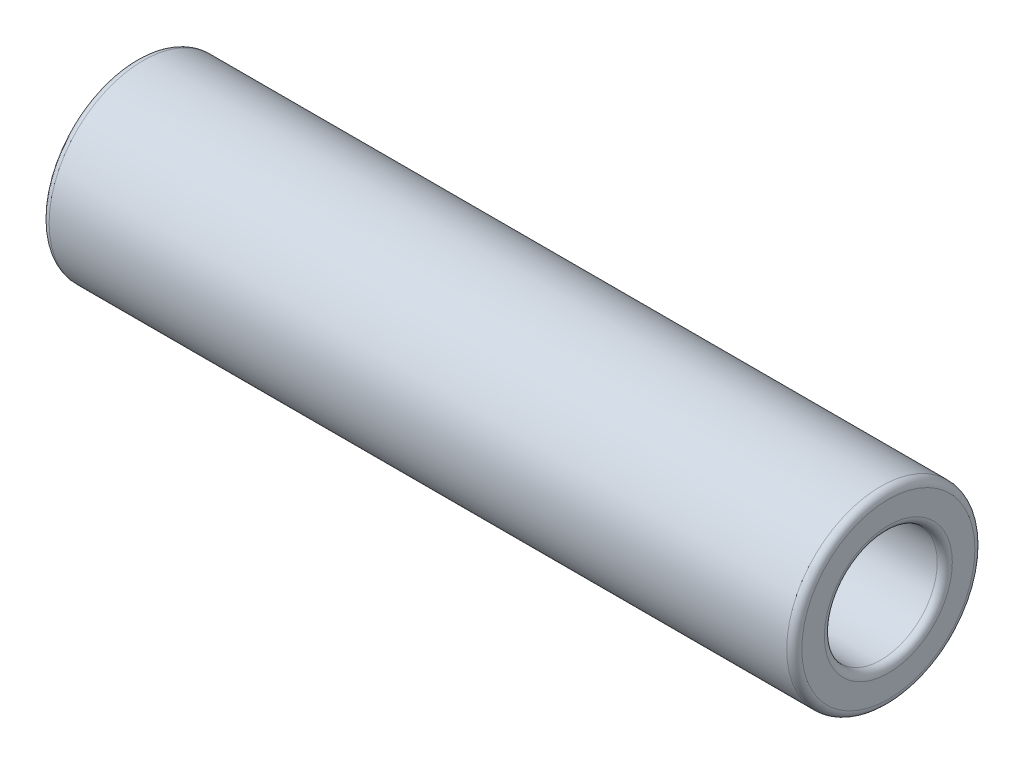
SolidWorks part; units mm, degrees
ref_plane "Front Plane" through (0, 0, 0) normal (0, 0, 1) x (1, 0, 0)
ref_plane "Top Plane" through (0, 0, 0) normal (0, 1, 0) x (1, 0, 0)
ref_plane "Right Plane" through (0, 0, 0) normal (1, 0, 0) x (0, 0, -1)
sketch "Sketch1" plane through (0, 0, 0) normal (1, 0, 0) x (0, 0, -1)
  circle A0 centre (0, 0) radius 6.25
  circle A1 centre (0, 0) radius 3.75
  dimension "D1" = 12.5
  dimension "D2" = 7.5
extrude "Boss-Extrude1" add sketch "Sketch1" along normal blind 50
fillet "Fillet1" radius 0.5 4 edges at (0, 0, -3.75) (0, 0, -6.25) (50, 0, -3.75) (50, 0, -6.25)
